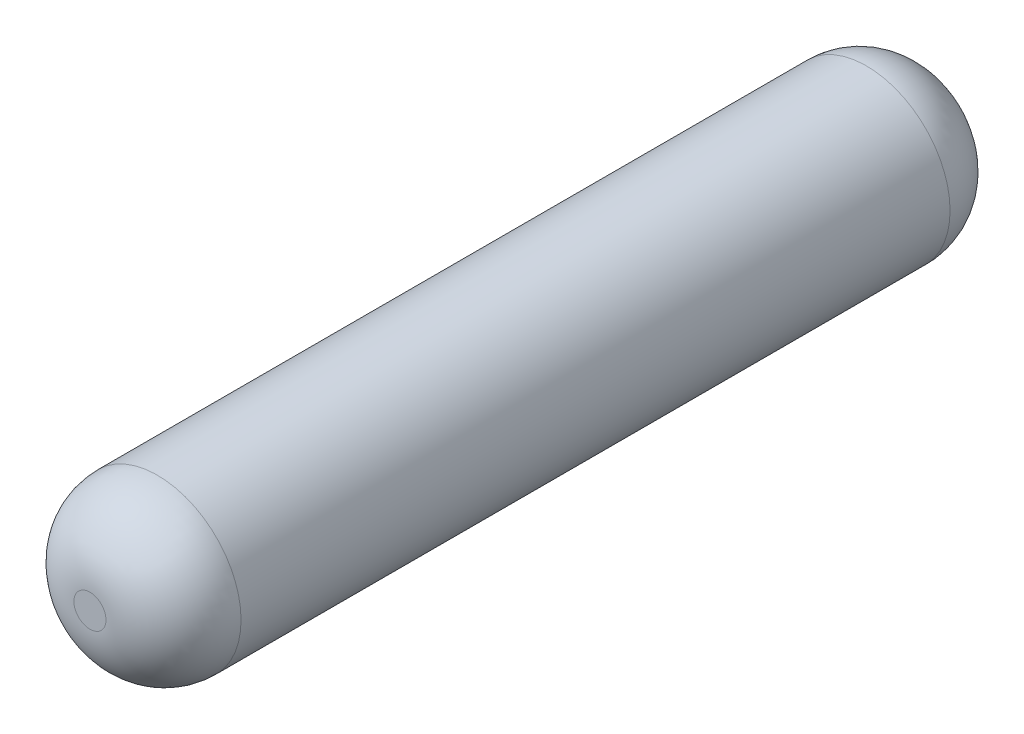
SolidWorks part; units mm, degrees
ref_plane "Front Plane" through (0, 0, 0) normal (0, 0, 1) x (1, 0, 0)
ref_plane "Top Plane" through (0, 0, 0) normal (0, 1, 0) x (1, 0, 0)
ref_plane "Right Plane" through (0, 0, 0) normal (1, 0, 0) x (0, 0, -1)
sketch "Sketch1" plane through (0, 0, 0) normal (0, 0, 1) x (1, 0, 0)
  circle A0 centre (0, 0) radius 2.475
  dimension "D1" = 4.95
extrude "Boss-Extrude1" add sketch "Sketch1" along normal blind 25 contours A0
fillet "Fillet1" radius 2 2 edges at (2.475, 0, 0) (2.475, 0, 25)
